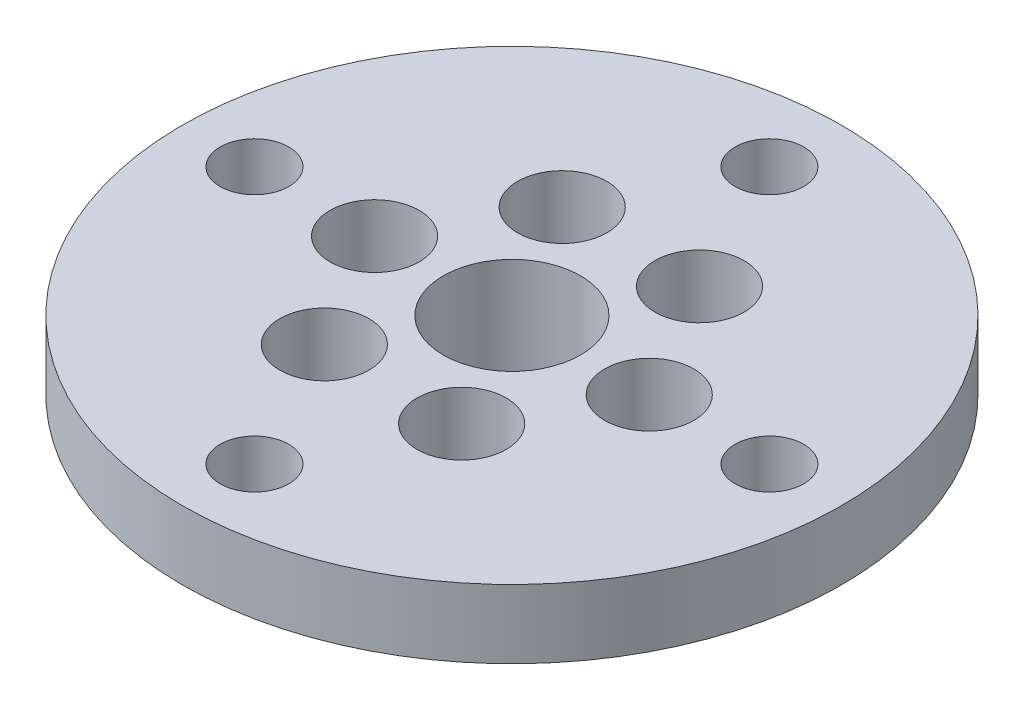
SolidWorks part; units mm, degrees
material "6061-T6 (SS)"
ref_plane "Front Plane" through (0, 0, 0) normal (0, 0, 1) x (1, 0, 0)
ref_plane "Top Plane" through (0, 0, 0) normal (0, 1, 0) x (1, 0, 0)
ref_plane "Right Plane" through (0, 0, 0) normal (1, 0, 0) x (0, 0, -1)
sketch "Sketch1" plane through (0, 0, 0) normal (0, 1, 0) x (1, 0, 0)
  circle A0 centre (0, 0) radius 15
  dimension "D1" = 30
extrude "Boss-Extrude1" add sketch "Sketch1" along normal blind 5
sketch "Sketch2" plane through (0, 0, 0) normal (0, 1, 0) x (1, 0, 0)
  circle A0 centre (0, 0) radius 13.5 construction
  circle A1 centre (-5, 8.6603) radius 1.25
  circle A2 centre (5, 8.6603) radius 1.25
  circle A3 centre (10, 0) radius 1.25
  circle A4 centre (5, -8.6603) radius 1.25
  circle A5 centre (-5, -8.6603) radius 1.25
  circle A6 centre (-10, 0) radius 1.25
  circle A7 centre (0, 0) radius 10 construction
  circle A8 centre (0, 0) radius 5
  point P3 (-10, 0)
  point P4 (-5, 8.6603)
  point P5 (5, 8.6603)
  point P6 (10, 0)
  point P7 (5, -8.6603)
  point P8 (-5, -8.6603)
  point P23 (0, 0)
  dimension "D1" = 27
  dimension "D2" = 2.5
  dimension "D4" = 20
  dimension "D5" = 10
  dimension "D3" = 6
sketch "Sketch3" plane through (0, 5, 0) normal (0, 1, 0) x (1, 0, 0)
  circle A0 centre (0, 0) radius 24
  dimension "D1" = 48
extrude "Boss-Extrude3" add sketch "Sketch3" along normal blind 5
extrude "Cut-Extrude1" cut sketch "Sketch2" along normal blind 11.5
sketch "Sketch4" plane through (0, 10, 0) normal (0, 1, 0) x (1, 0, 0)
  circle A1 centre (10, 0) radius 3.25
  circle A2 centre (5, 8.6603) radius 3.25
  circle A3 centre (5, 8.6603) radius 3.25
  circle A4 centre (5, -8.6603) radius 3.25
  circle A5 centre (-5, -8.6603) radius 3.25
  circle A6 centre (-10, 0) radius 3.25
  circle A7 centre (-5, 8.6603) radius 3.25
  point P15 (0, 0)
  dimension "D1" = 2
  dimension "D2" = 6
extrude "Cut-Extrude2" cut sketch "Sketch4" against normal offset from surface (6 mm away) 4 up to face at (5, 0, 9.9103)
sketch "Sketch5" plane through (0, 10, 0) normal (0, 1, 0) x (1, 0, 0)
  line L0 (0, 0) -> (0, 18.75) construction
  circle A0 centre (0, 0) radius 18.75 construction
  circle A1 centre (0, 18.75) radius 2.5
  circle A2 centre (18.75, 0) radius 2.5
  circle A3 centre (0, -18.75) radius 2.5
  circle A4 centre (-18.75, 0) radius 2.5
  point P14 (0, 0)
  dimension "D1" = 37.5
  dimension "D2" = 5
  dimension "D3" = 4
extrude "Cut-Extrude3" cut sketch "Sketch5" against normal offset from surface (6.5 mm away) 3.5 up to face at (5, 0, 9.9103)
